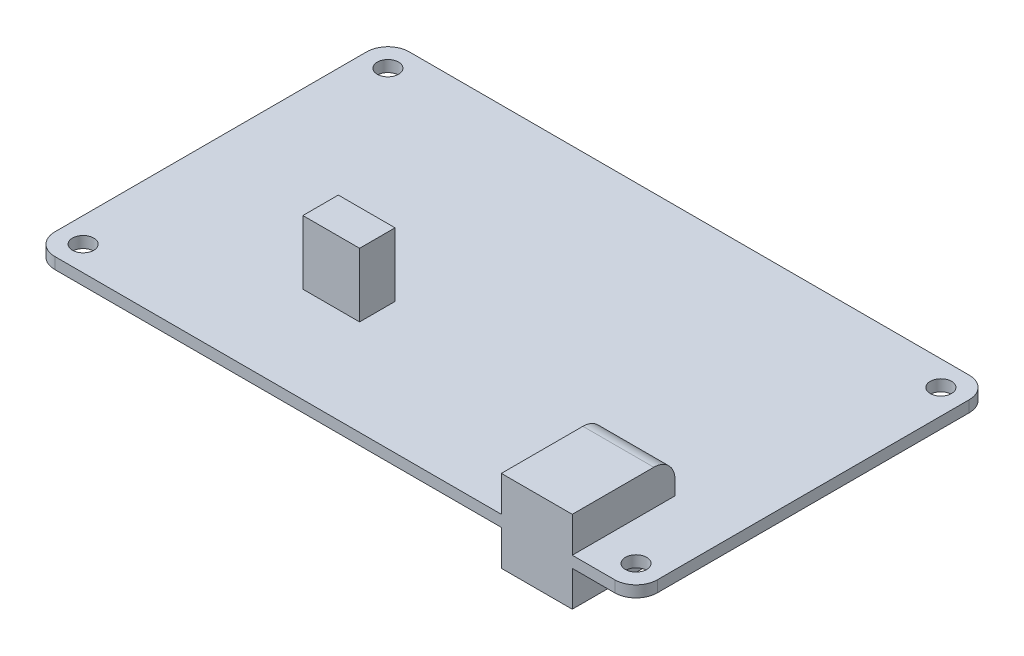
SolidWorks part; units mm, degrees
ref_plane "前视基准面" through (0, 0, 0) normal (0, 0, 1) x (1, 0, 0)
ref_plane "上视基准面" through (0, 0, 0) normal (0, 1, 0) x (1, 0, 0)
ref_plane "右视基准面" through (0, 0, 0) normal (1, 0, 0) x (0, 0, -1)
sketch "草图1" plane through (0, 0, 0) normal (0, 1, 0) x (1, 0, 0)
  line L1 (-42.5, 25) -> (42.5, 25)
  line L2 (-42.5, 25) -> (-42.5, -25)
  line L3 (-42.5, -25) -> (42.5, -25)
  line L4 (42.5, 25) -> (42.5, -25)
  line L5 (-42.5, 25) -> (42.5, -25) construction
  line L6 (-42.5, -25) -> (42.5, 25) construction
  circle A0 centre (-39, 21.5) radius 1.5
  circle A1 centre (39, 21.5) radius 1.5
  circle A2 centre (39, -21.5) radius 1.5
  circle A3 centre (-39, -21.5) radius 1.5
  point P0 (0, 0)
  dimension "D3" = 3
  dimension "D4" = 3
  dimension "D5" = 3
  dimension "D6" = 3
  dimension "D1" = 85
  dimension "D2" = 50
  dimension "D7" = 3.5
  dimension "D8" = 3.5
  dimension "D9" = 3.5
  dimension "D10" = 3.5
  dimension "D11" = 3.5
  dimension "D12" = 3.5
  dimension "D13" = 3.5
  dimension "D14" = 3.5
extrude "凸台-拉伸1" add sketch "草图1" along normal blind 1.6
fillet "圆角1" radius 3 4 edges at (42.5, 0.8, -25) (42.5, 0.8, 25) (-42.5, 0.8, 25) (-42.5, 0.8, -25)
sketch "草图2" plane through (0, 1.6, 0) normal (0, 1, 0) x (1, 0, 0)
  line L0 (-39.5, -25) -> (39.5, -25) construction
  line L1 (33.5, -25) -> (23.5, -25)
  line L2 (33.5, -25) -> (33.5, -10.5)
  line L3 (33.5, -10.5) -> (23.5, -10.5)
  line L4 (23.5, -25) -> (23.5, -10.5)
  line L5 (42.5, -22) -> (42.5, 22) construction
  dimension "D1" = 9
  dimension "D2" = 10
  dimension "D3" = 14.5
extrude "凸台-拉伸2" add sketch "草图2" along normal blind 5
sketch "草图3" plane through (0, 1.6, 0) normal (0, 1, 0) x (1, 0, 0)
  line L0 (-39.5, -25) -> (23.5, -25) construction
  line L1 (-18, -6.5) -> (-10, -6.5)
  line L2 (-18, -6.5) -> (-18, -11.5)
  line L3 (-18, -11.5) -> (-10, -11.5)
  line L4 (-10, -6.5) -> (-10, -11.5)
  line L5 (-42.5, 22) -> (-42.5, -22) construction
  dimension "D1" = 5
  dimension "D2" = 8
  dimension "D3" = 13.5
  dimension "D4" = 24.5
extrude "凸台-拉伸3" add sketch "草图3" along normal blind 9
sketch "草图4" plane through (0, 0, 0) normal (0, -1, 0) x (1, 0, 0)
  line L0 (-39.5, 25) -> (39.5, 25) construction
  line L1 (33.5, 25) -> (23.5, 25)
  line L2 (33.5, 25) -> (33.5, 10.5)
  line L3 (33.5, 10.5) -> (23.5, 10.5)
  line L4 (23.5, 25) -> (23.5, 10.5)
  line L5 (42.5, 22) -> (42.5, -22) construction
  dimension "D1" = 9
  dimension "D2" = 10
  dimension "D3" = 14.5
extrude "凸台-拉伸4" add sketch "草图4" along normal blind 5
fillet "圆角2" radius 3 2 edges at (28.5, -5, 10.5) (28.5, 6.6, 10.5)
